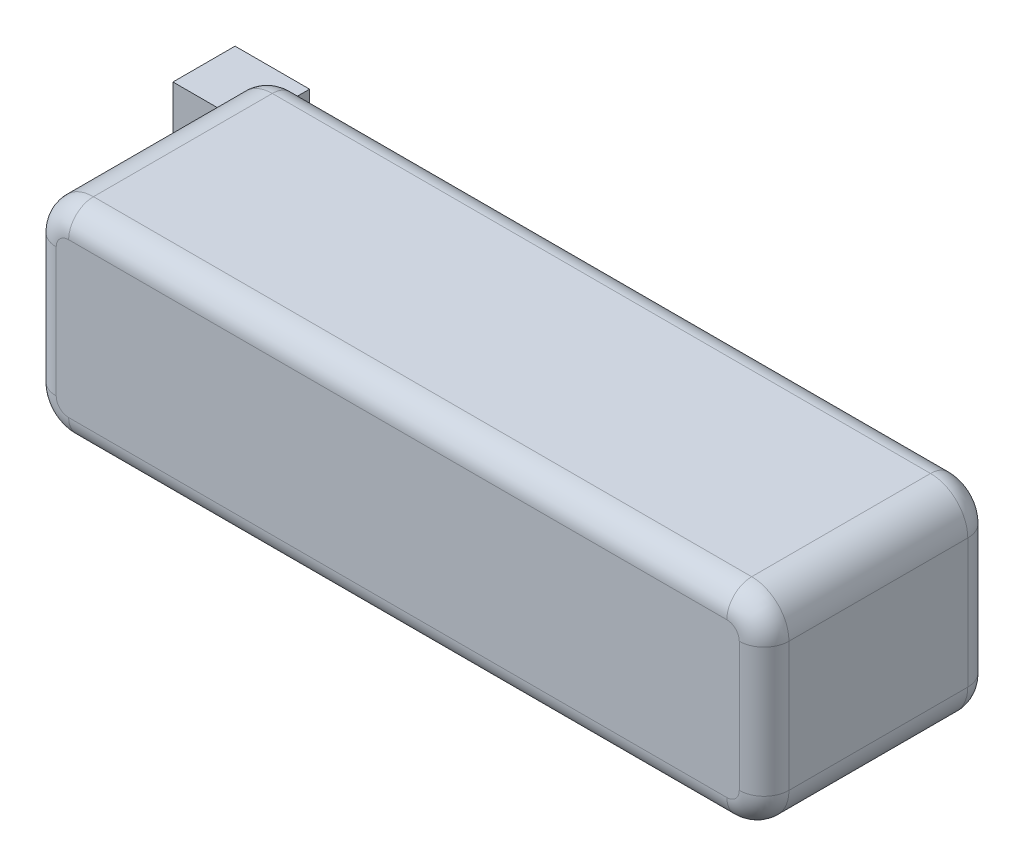
SolidWorks part; units mm, degrees
ref_plane "Front Plane" through (0, 0, 0) normal (0, 0, 1) x (1, 0, 0)
ref_plane "Top Plane" through (0, 0, 0) normal (0, 1, 0) x (1, 0, 0)
ref_plane "Right Plane" through (0, 0, 0) normal (1, 0, 0) x (0, 0, -1)
sketch "Sketch1" plane through (0, 0, 0) normal (0, 1, 0) x (1, 0, 0)
  line L1 (0, 0) -> (74.93, 0)
  line L2 (0, 0) -> (0, -23.368)
  line L3 (0, -23.368) -> (74.93, -23.368)
  line L4 (74.93, 0) -> (74.93, -23.368)
  dimension "D1" = 74.93
  dimension "D2" = 23.368
extrude "Boss-Extrude1" add sketch "Sketch1" along normal blind 20.828
sketch "Sketch2" plane through (0, 0, 0) normal (-1, 0, 0) x (0, 0, 1)
  line L0 (0, 20.828) -> (0, 0) construction
  line L1 (0, 15.494) -> (1.27, 15.494)
  line L2 (0, 15.494) -> (0, 5.334)
  line L3 (0, 5.334) -> (1.27, 5.334)
  line L4 (1.27, 15.494) -> (1.27, 5.334)
  line L5 (3.34, 20.828) -> (3.34, 15.494) construction
  line L6 (0, 20.828) -> (23.368, 20.828) construction
  line L7 (3.34, 5.334) -> (3.34, 0) construction
  line L8 (0, 0) -> (23.368, 0) construction
  line L10 (0, 15.494) -> (-5.08, 15.494)
  line L11 (0, 15.494) -> (0, 5.334)
  line L12 (0, 5.334) -> (-5.08, 5.334)
  line L13 (-5.08, 15.494) -> (-5.08, 5.334)
  line M4 (0, 20.828) -> (0, 0)
  dimension "D1" = 10.16
  dimension "D2" = 5.08
  dimension "D3" = 1.27
extrude "Boss-Extrude2" add sketch "Sketch2" along normal blind 7.62 contours L10 L13 L12 M4 | L4 L1 L3 M4
fillet "Fillet1" radius 2.54 2 edges at (0, 10.414, 1.27) (0, 10.414, 0)
fillet "Fillet2" radius 3.81 4 edges at (0, 20.828, 11.684) (74.93, 20.828, 11.684) (74.93, 0, 11.684) (0, 0, 11.684)
fillet "Fillet3" radius 2.54 8 edges at (1.1159, 1.1159, 23.368) (0, 10.414, 23.368) (1.1159, 19.7121, 23.368) (37.465, 20.828, 23.368) (73.8141, 19.7121, 23.368) (74.93, 10.414, 23.368) (73.8141, 1.1159, 23.368) (37.465, 0, 23.368)
fillet "Fillet4" radius 2.54 9 edges at (0, 16.256, 0) (1.1159, 19.7121, 0) (37.465, 20.828, 0) (73.8141, 19.7121, 0) (74.93, 10.414, 0) (73.8141, 1.1159, 0) (0, 4.572, 0) (1.1159, 1.1159, 0) (37.465, 0, 0)
